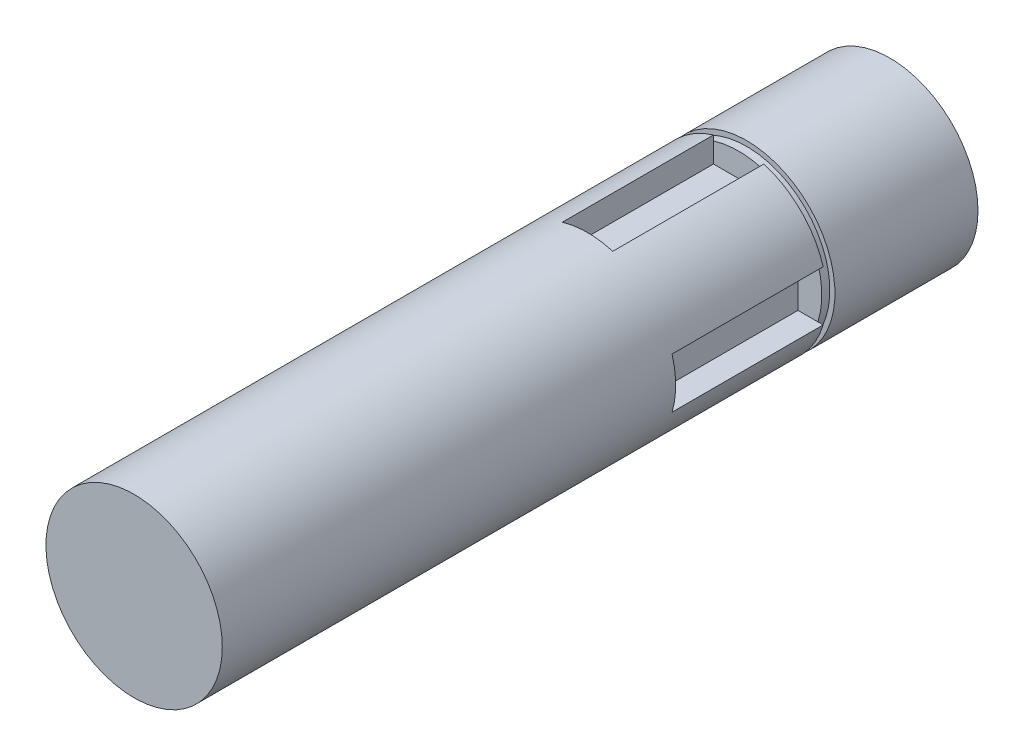
SolidWorks part; units mm, degrees
ref_plane "Front Plane" through (0, 0, 0) normal (0, 0, 1) x (1, 0, 0)
ref_plane "Top Plane" through (0, 0, 0) normal (0, 1, 0) x (1, 0, 0)
ref_plane "Right Plane" through (0, 0, 0) normal (1, 0, 0) x (0, 0, -1)
sketch "Sketch1" plane through (0, 0, 0) normal (0, 0, 1) x (1, 0, 0)
  circle A0 centre (0, 0) radius 17.5
  dimension "D1" = 35
extrude "Boss-Extrude1" add sketch "Sketch1" along normal blind 150
sketch "Sketch3" plane through (0, 0, 0) normal (0, 0, 1) x (1, 0, 0)
  line L0 (-5, 16.7705) -> (-5, 11.7705)
  line L1 (-5, 11.7705) -> (5, 11.7705)
  line L2 (5, 11.7705) -> (5, 16.7705)
  line L3 (16.7705, 5) -> (11.7705, 5)
  line L4 (11.7705, 5) -> (11.7705, -5)
  line L5 (11.7705, -5) -> (16.7705, -5)
  circle A0 centre (0, 0) radius 17.5 construction
  arc A1 (-5, 16.7705) -> (5, 16.7705) centre (0, 0) cw
  arc A2 (16.7705, 5) -> (16.7705, -5) centre (0, 0) cw
  dimension "D1" = 5
  dimension "D2" = 10
extrude "Cut-Extrude1" cut sketch "Sketch3" along normal blind 30 from offset 30
sketch "Sketch4" plane through (0, 0, 0) normal (1, 0, 0) x (0, 0, -1)
  line L0 (0, 0) -> (-150, 0) construction
  line L1 (-150, 17.5) -> (-150, -17.5) construction
  line L3 (-30, 17.5) -> (-28.4, 17.5)
  line L4 (-30, 17.5) -> (-30, 16.5)
  line L5 (-30, 16.5) -> (-28.4, 16.5)
  line L6 (-28.4, 17.5) -> (-28.4, 16.5)
  point P10 (-30, 17.5)
  dimension "D1" = 1.6
  dimension "D2" = 1
revolve "Cut-Revolve1" cut sketch "Sketch4" angle 360 about L0
